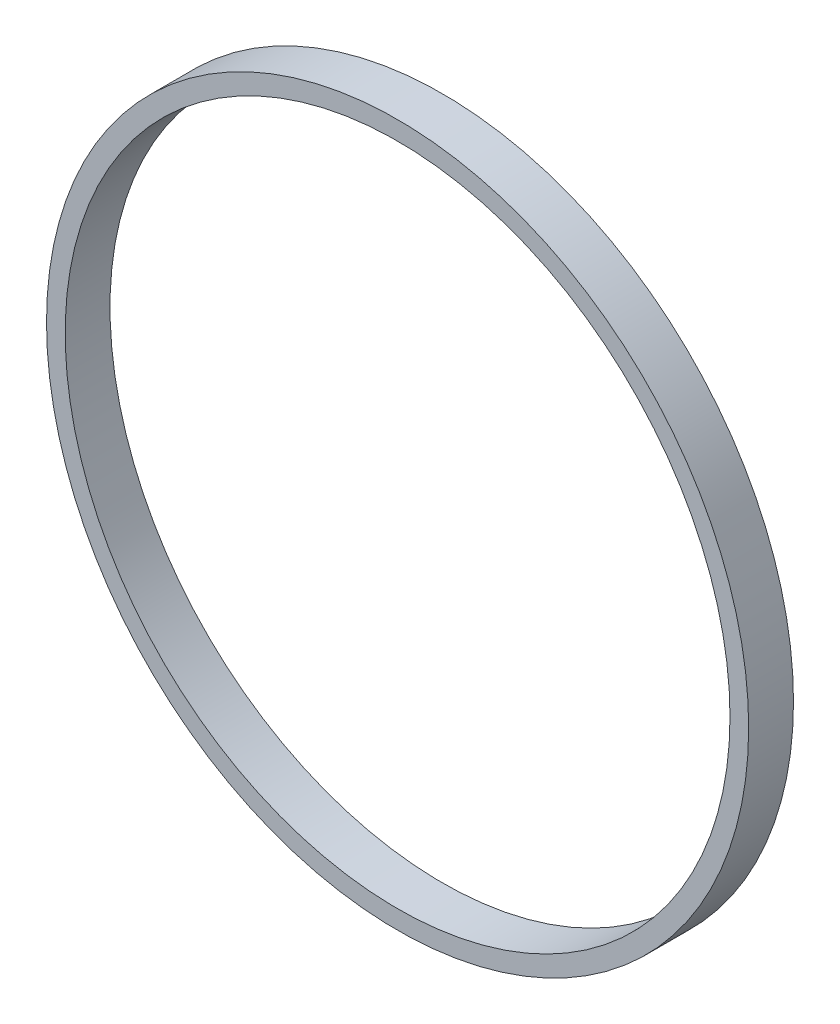
SolidWorks part; units mm, degrees
ref_plane "Front Plane" through (0, 0, 0) normal (0, 0, 1) x (1, 0, 0)
ref_plane "Top Plane" through (0, 0, 0) normal (0, 1, 0) x (1, 0, 0)
ref_plane "Right Plane" through (0, 0, 0) normal (1, 0, 0) x (0, 0, -1)
sketch "Sketch1" plane through (0, 0, 0) normal (0, 0, 1) x (1, 0, 0)
  circle A0 centre (0, 0) radius 22.25
  circle A1 centre (0, 0) radius 23.5
  dimension "D1" = 47
  dimension "D2" = 44.5
extrude "Boss-Extrude1" add sketch "Sketch1" along normal blind 3
